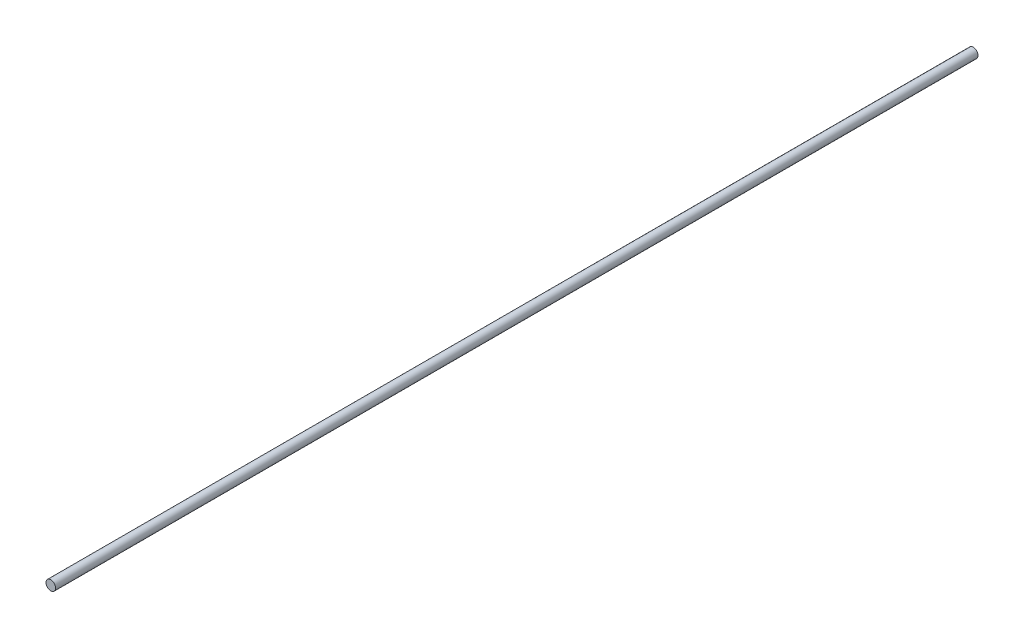
SolidWorks part; units mm, degrees
ref_plane "Front Plane" through (0, 0, 0) normal (0, 0, 1) x (1, 0, 0)
ref_plane "Top Plane" through (0, 0, 0) normal (0, 1, 0) x (1, 0, 0)
ref_plane "Right Plane" through (0, 0, 0) normal (1, 0, 0) x (0, 0, -1)
sketch "Sketch1" plane through (0, 0, 0) normal (0, 0, 1) x (1, 0, 0)
  line L1 (-4.7625, 0) -> (4.7625, 0) construction
  dimension "OD" = 9.525
sketch "Sketch2" plane through (0, 0, 0) normal (1, 0, 0) x (0, 0, -1)
  line L0 (457.2, 0) -> (-457.2, 0)
  point P0 (-342.9, 0)
  point P3 (342.9, 0)
  point P4 (0, 0)
  dimension "Length" = 914.4
  dimension "D1" = 114.3
  dimension "D2" = 114.3
sketch "Sketch3" plane through (0, 0, 0) normal (0, 0, 1) x (1, 0, 0)
  circle A0 centre (0, 0) radius 4.7625
extrude "Boss-Extrude1" add sketch "Sketch3" along normal up to vertex (457.2 mm away) and the other way up to vertex (457.2 mm away) up to point (0, 0, 457.2) other way up to point (0, 0, -457.2)
equation "\"D1@Sketch2\"=\"Length@Sketch2\"/8"
equation "\"D2@Sketch2\"=\"D1@Sketch2\""
